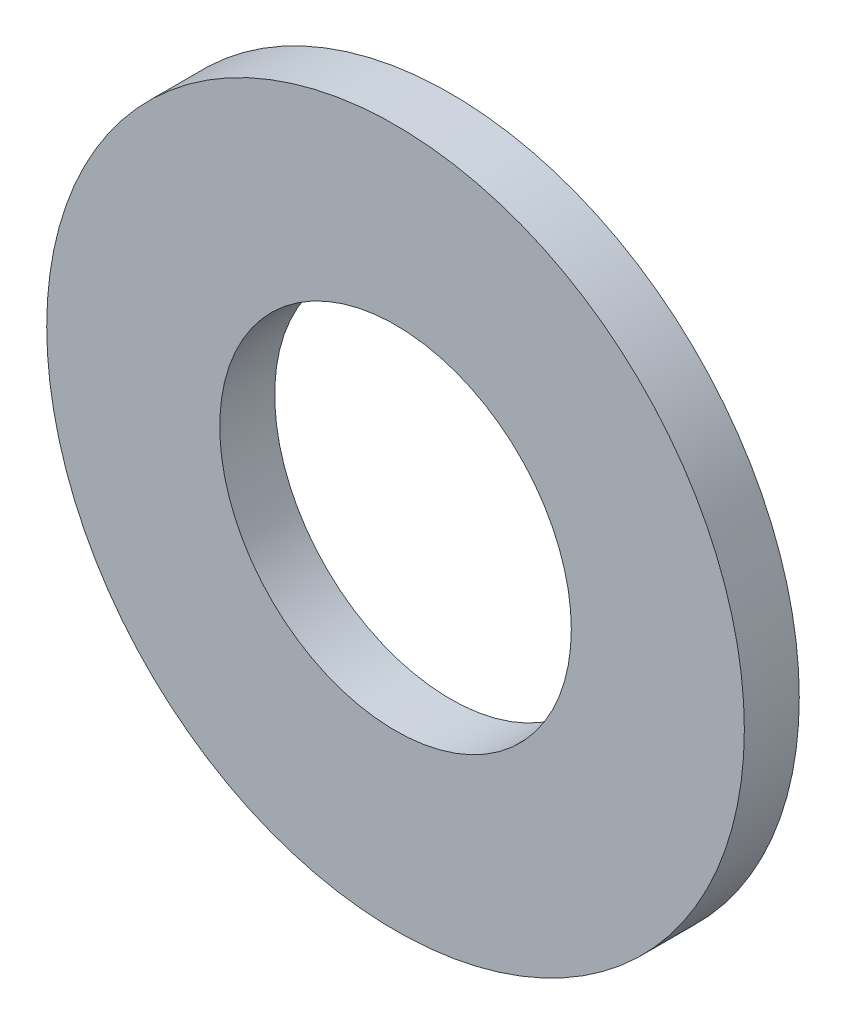
SolidWorks part; units mm, degrees
ref_plane "Front Plane" through (0, 0, 0) normal (0, 0, 1) x (1, 0, 0)
ref_plane "Top Plane" through (0, 0, 0) normal (0, 1, 0) x (1, 0, 0)
ref_plane "Right Plane" through (0, 0, 0) normal (1, 0, 0) x (0, 0, -1)
sketch "Sketch1" plane through (0, 0, 0) normal (0, 0, 1) x (1, 0, 0)
  circle A0 centre (0, 0) radius 1.6
  circle A1 centre (0, 0) radius 3.175
  dimension "ID" = 3.2
  dimension "OD" = 6.35
extrude "Extrude1" add sketch "Sketch1" against normal blind 0.5
